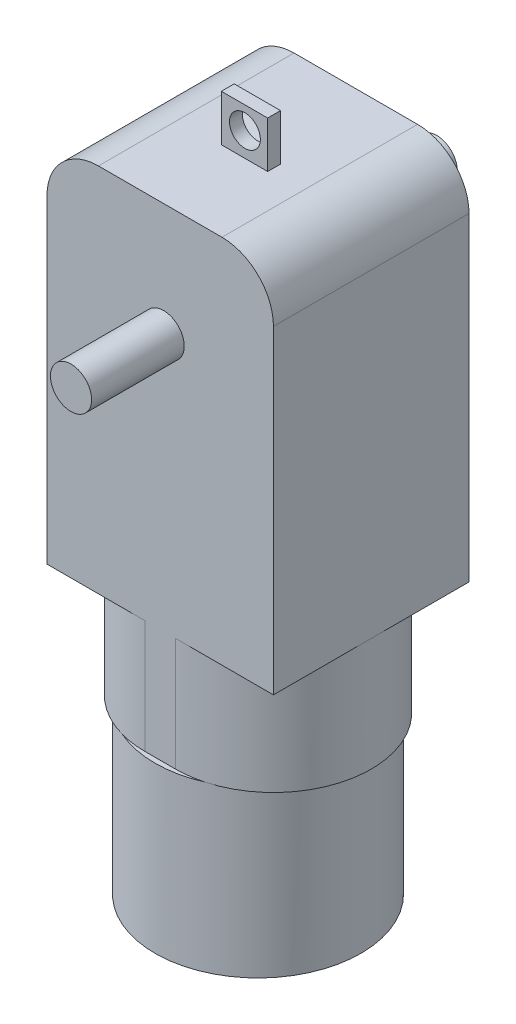
SolidWorks part; units mm, degrees
ref_plane "正面" through (0, 0, 0) normal (0, 0, 1) x (1, 0, 0)
ref_plane "平面" through (0, 0, 0) normal (0, 1, 0) x (1, 0, 0)
ref_plane "右側面" through (0, 0, 0) normal (1, 0, 0) x (0, 0, -1)
sketch "ｽｹｯﾁ1" plane through (0, 0, 0) normal (0, 0, 1) x (1, 0, 0)
  line L1 (0, 0) -> (22, 0)
  line L2 (0, 0) -> (0, 36)
  line L3 (0, 36) -> (22, 36)
  line L4 (22, 0) -> (22, 36)
  dimension "D1" = 36
  dimension "D2" = 22
extrude "ﾎﾞｽ - 押し出し1" add sketch "ｽｹｯﾁ1" along normal blind 19
ref_plane "平面1" through (0, 0, 10) normal (0, 0, 1) x (1, 0, 0)
sketch "ｽｹｯﾁ2" plane through (0, 0, 10) normal (0, 0, 1) x (1, 0, 0)
  line L0 (22, 36) -> (0, 36) construction
  line L1 (9.19, 36) -> (13.69, 36)
  line L2 (9.19, 36) -> (9.19, 40.5)
  line L3 (9.19, 40.5) -> (13.69, 40.5)
  line L4 (13.69, 36) -> (13.69, 40.5)
  dimension "D1" = 4.5
  dimension "D2" = 4.5
extrude "ﾎﾞｽ - 押し出し2" add sketch "ｽｹｯﾁ2" along normal blind 1.25
sketch "ｽｹｯﾁ3" plane through (0, 0, 11.25) normal (0, 0, 1) x (1, 0, 0)
  circle A0 centre (11.4784, 38.3422) radius 1.5
  dimension "D1" = 3
extrude "ｶｯﾄ - 押し出し1" cut sketch "ｽｹｯﾁ3" against normal through all
sketch "ｽｹｯﾁ4" plane through (0, 0, 0) normal (0, -1, 0) x (1, 0, 0)
  line L0 (9.5, 9.5) -> (12.5, 9.5) construction
  line L1 (9.5, 19) -> (12.5, 19)
  line L2 (9.5, 0) -> (12.5, 0)
  line L3 (22, 19) -> (22, 0) construction
  line L4 (0, 19) -> (0, 0) construction
  line L5 (0, 19) -> (22, 19) construction
  arc A0 (9.5, 19) -> (9.5, 0) centre (9.5, 9.5) ccw
  arc A1 (12.5, 0) -> (12.5, 19) centre (12.5, 9.5) ccw
  point P2 (11, 9.5)
  point P7 (22, 9.5)
  point P10 (0, 9.5)
extrude "ﾎﾞｽ - 押し出し3" add sketch "ｽｹｯﾁ4" along normal blind 11
sketch "ｽｹｯﾁ5" plane through (0, -11, 0) normal (0, -1, 0) x (1, 0, 0)
  circle A0 centre (11, 9.5) radius 10
  point P4 (0, 0)
  dimension "D1" = 20
extrude "ﾎﾞｽ - 押し出し4" add sketch "ｽｹｯﾁ5" along normal blind 16
fillet "ﾌｨﾚｯﾄ1" radius 5 2 edges at (22, 36, 9.5) (0, 36, 9.5)
sketch "ｽｹｯﾁ6" plane through (0, 0, 0) normal (0, 0, -1) x (-1, 0, 0)
  line L0 (-17, 36) -> (-5, 36) construction
  circle A0 centre (-9.8688, 25) radius 2
  dimension "D2" = 4
  dimension "D1" = 11
extrude "ﾎﾞｽ - 押し出し5" add sketch "ｽｹｯﾁ6" along normal blind 9
sketch "ｽｹｯﾁ7" plane through (0, 0, 19) normal (0, 0, 1) x (1, 0, 0)
  line L0 (17, 36) -> (5, 36) construction
  circle A0 centre (11.3351, 25) radius 2
  dimension "D2" = 4
  dimension "D1" = 11
extrude "ﾎﾞｽ - 押し出し6" add sketch "ｽｹｯﾁ7" along normal blind 9
